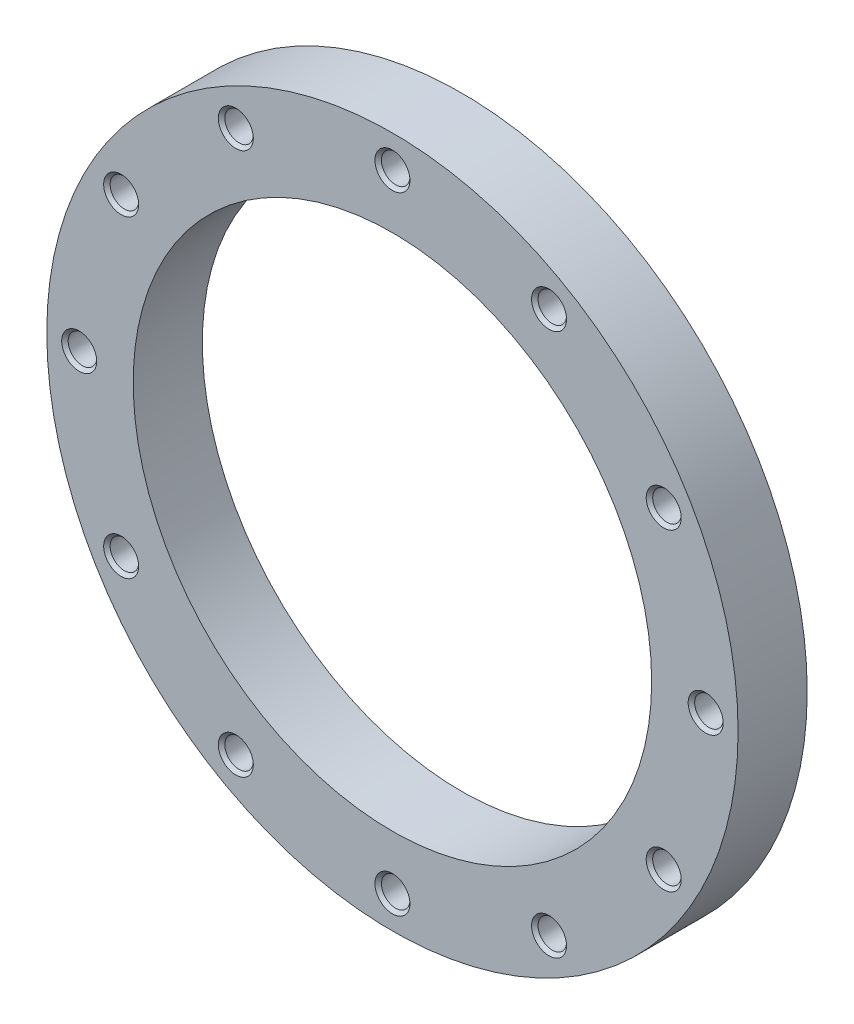
SolidWorks part; units mm, degrees
ref_plane "Front Plane" through (0, 0, 0) normal (0, 0, 1) x (1, 0, 0)
ref_plane "Top Plane" through (0, 0, 0) normal (0, 1, 0) x (1, 0, 0)
ref_plane "Right Plane" through (0, 0, 0) normal (1, 0, 0) x (0, 0, -1)
sketch "Sketch1" plane through (0, 0, 0) normal (0, 0, 1) x (1, 0, 0)
  line L0 (-1000, 0) -> (49000, 0) construction
  line L1 (0, -1000) -> (0, 49000) construction
  circle A0 centre (0, 0) radius 40
  circle A1 centre (0, 0) radius 30
  circle A2 centre (0, 0) radius 36.25 construction
  point P4 (0, 36.25)
  dimension "D1" = 80
  dimension "D2" = 60
  dimension "D3" = 72.5
extrude "Boss-Extrude1" add sketch "Sketch1" against normal blind 8
hole_wizard "M4x0.7 Tapped Hole1" positions "Sketch7" profile "Sketch8" tap size "M4x0.7" standard "ANSI Metric" end condition through all
sketch "Sketch7" plane through (0, 0, 0) normal (0, 0, 1) x (1, 0, 0)
  point P0 (0, 36.25)
cosmetic thread "Hole Thread1" parameters "D2"=4
sketch "Sketch8" plane through (0, 36.25, 0) normal (1, 0, 0) x (0, -1, 0)
  line L0 (0, 0) -> (0, 8)
  line L1 (0, 8) -> (1.65, 8)
  line L2 (1.65, 8) -> (1.65, 0.375)
  line L3 (1.65, 0.375) -> (2.025, 0)
  line L5 (2.025, 0) -> (0, 0)
  line L6 (-1.65, 0.375) -> (-2.025, 0) construction
  line L11 (0, -6.35) -> (0, 107.95) construction
  dimension "Thru Tap Drill Dia." = 3.3
  dimension "Thru Tap Drill Depth" = 8
  dimension "Near C'Sink Dia." = 4.05
  dimension "Near C'Sink Angle" = 90
sketch "Sketch9" plane through (0, 0, 0) normal (1, 0, 0) x (0, 0, -1)
  line L0 (-1000, 0) -> (49000, 0) construction
pattern_circular "CirPattern1" count 12 over 360 about axis through (0, 0, 0) along (0, 0, 1) of "M4x0.7 Tapped Hole1"
cosmetic thread "Hole Thread2" parameters "D2"=4
cosmetic thread "Hole Thread3" parameters "D2"=4
cosmetic thread "Hole Thread4" parameters "D2"=4
cosmetic thread "Hole Thread5" parameters "D2"=4
cosmetic thread "Hole Thread6" parameters "D2"=4
cosmetic thread "Hole Thread7" parameters "D2"=4
cosmetic thread "Hole Thread8" parameters "D2"=4
cosmetic thread "Hole Thread9" parameters "D2"=4
cosmetic thread "Hole Thread10" parameters "D2"=4
cosmetic thread "Hole Thread11" parameters "D2"=4
cosmetic thread "Hole Thread12" parameters "D2"=4
